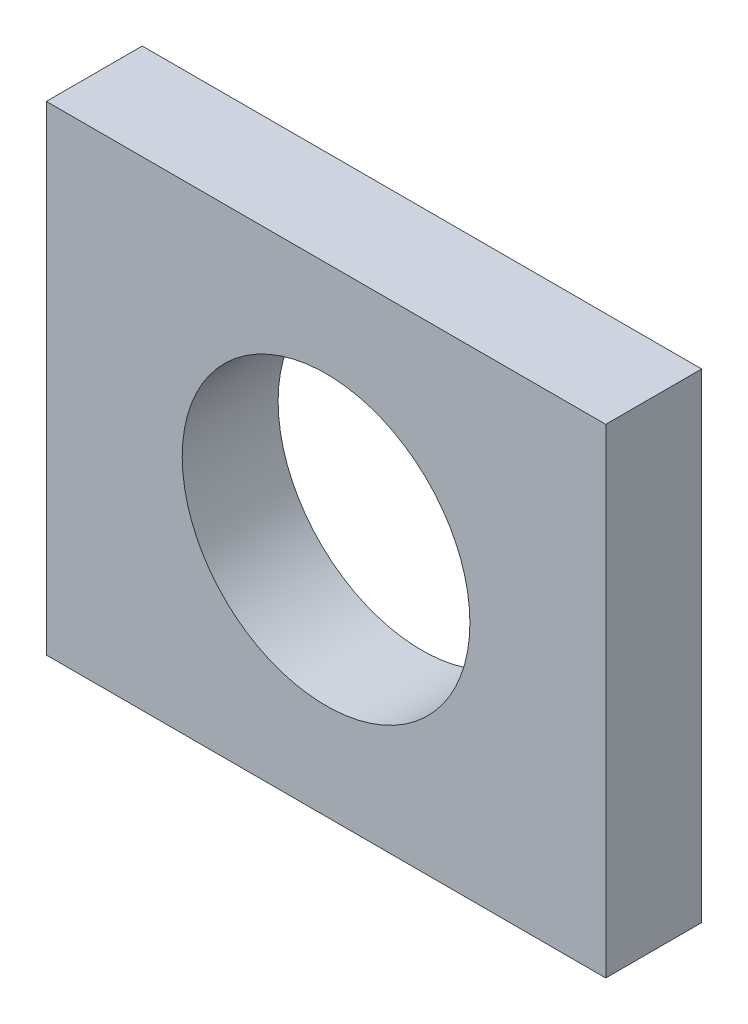
SolidWorks part; units mm, degrees
ref_plane "前视基准面" through (0, 0, 0) normal (0, 0, 1) x (1, 0, 0)
ref_plane "上视基准面" through (0, 0, 0) normal (0, 1, 0) x (1, 0, 0)
ref_plane "右视基准面" through (0, 0, 0) normal (1, 0, 0) x (0, 0, -1)
sketch "草图1" plane through (0, 0, 0) normal (0, 0, 1) x (1, 0, 0)
  line L0 (-50, 0) -> (50, 0) construction
  line L1 (-35, -30) -> (35, -30)
  line L2 (-35, -30) -> (-35, 30)
  line L3 (-35, 30) -> (35, 30)
  line L4 (35, -30) -> (35, 30)
  line L5 (-35, -30) -> (35, 30) construction
  line L6 (-35, 30) -> (35, -30) construction
  line L7 (0, 0) -> (0, -34.4476) construction
  point P0 (0, 0)
  point P12 (0, 0)
  dimension "D1" = 70
  dimension "D2" = 60
  dimension "D3" = 100
extrude "凸台-拉伸1" add sketch "草图1" along normal blind 12
sketch "草图2" plane through (0, 0, 0) normal (0, 0, -1) x (-1, 0, 0)
  circle A0 centre (0, 0) radius 18
  dimension "D1" = 36
extrude "切除-拉伸1" cut sketch "草图2" against normal up to next
ref_plane "基准面1" through (0, 0, 0) normal (1, 0, 0) x (0, 0, -1)
sketch "草图3" plane through (35, 0, 0) normal (1, 0, 0) x (0, 0, -1)
  line L0 (-12, -30) -> (-12, 30) construction
  line L1 (-12, 30) -> (0, 30)
  line L2 (-12, 30) -> (-12, -30)
  line L3 (-12, -30) -> (0, -30)
  line L4 (0, 30) -> (0, -30)
  line L5 (-12, 30) -> (0, -30) construction
  line L6 (-12, -30) -> (0, 30) construction
  line L7 (-12, -30) -> (0, -30) construction
  point P0 (-6, 0)
